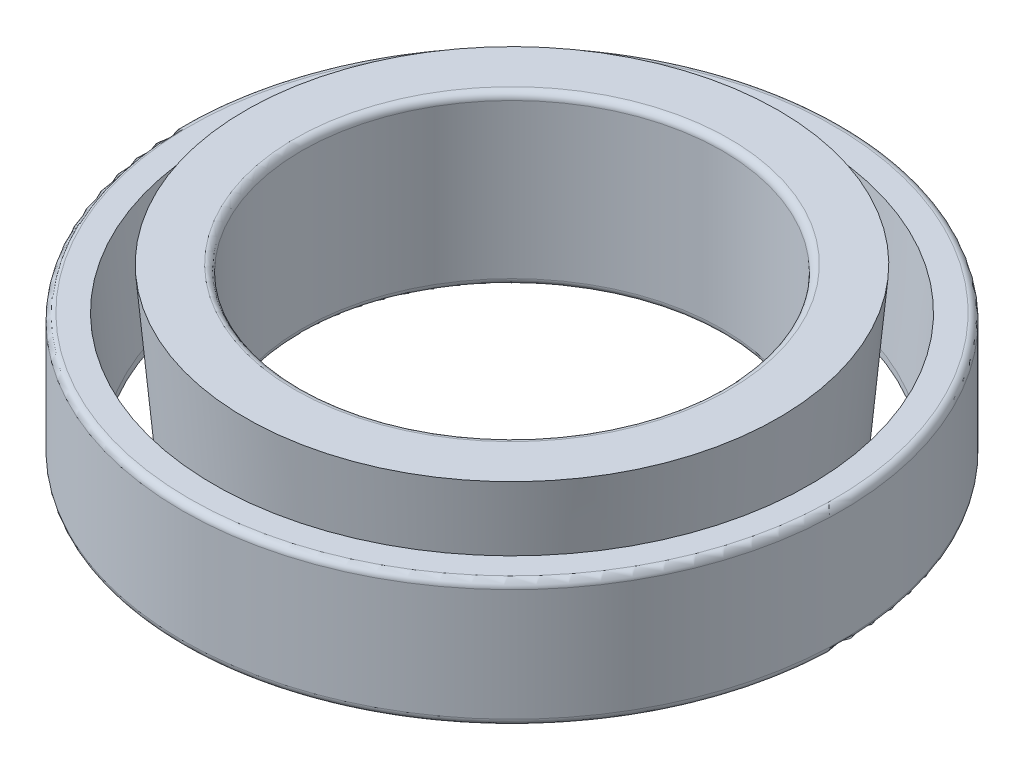
SolidWorks part; units mm, degrees
ref_plane "Ebene vorne" through (0, 0, 0) normal (0, 0, 1) x (1, 0, 0)
ref_plane "Ebene oben" through (0, 0, 0) normal (0, 1, 0) x (1, 0, 0)
ref_plane "Ebene rechts" through (0, 0, 0) normal (1, 0, 0) x (0, 0, -1)
sketch "Skizze1" plane through (0, 0, 0) normal (0, 0, 1) x (1, 0, 0)
  line L0 (0, 0) -> (0, 34.8688) construction
  line L1 (15, -0.0132) -> (15, 11.9868)
  line L2 (15, 11.9868) -> (19, 11.9868)
  line L6 (21.2554, 9) -> (23.5, 9)
  line L7 (23.5, 9) -> (23.5, 0)
  line L8 (23.5, 0) -> (20.5837, 0)
  line L9 (20.5837, 0) -> (20.5837, 0.4868)
  line L12 (17.9465, -0.0132) -> (15, -0.0132)
  line L13 (19, 11.9868) -> (17.9465, -0.0132)
  line L14 (21.2554, 9) -> (20.5837, 0.4868)
  point P17 (20.88, 0.4915)
  point P18 (20.936, 0.4868)
  dimension "D1" = 30
  dimension "D2" = 47
  dimension "D3" = 12
  dimension "D4" = 9
  dimension "D5" = 38
revolve "Rotation1" add sketch "Skizze1" angle 360 about L0
fillet "Verrundung1" radius 0.5 2 edges at (0, -0.0132, -15) (0, 11.9868, -15)
fillet "Verrundung2" radius 0.5 2 edges at (0, 0, -23.5) (0, 9, -23.5)
